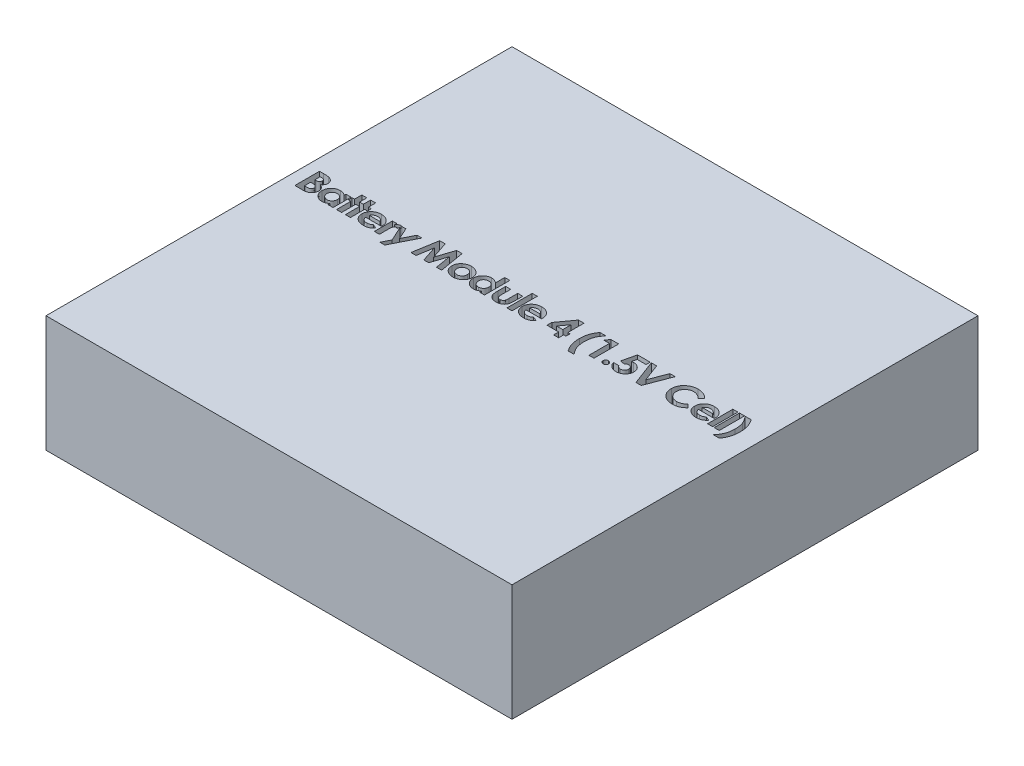
SolidWorks part; units mm, degrees
ref_plane "Front Plane" through (0, 0, 0) normal (0, 0, 1) x (1, 0, 0)
ref_plane "Top Plane" through (0, 0, 0) normal (0, 1, 0) x (1, 0, 0)
ref_plane "Right Plane" through (0, 0, 0) normal (1, 0, 0) x (0, 0, -1)
sketch "Sketch1" plane through (0, 0, 0) normal (0, 1, 0) x (1, 0, 0)
  line L1 (0, 0) -> (60, 0)
  line L2 (0, 0) -> (0, -60)
  line L3 (0, -60) -> (60, -60)
  line L4 (60, 0) -> (60, -60)
  dimension "D1" = 60
  dimension "D2" = 60
extrude "Boss-Extrude1" add sketch "Sketch1" along normal blind 15
sketch "Sketch2" plane through (0, 15, 0) normal (0, 1, 0) x (1, 0, 0)
  text T0 "<b>Battery Module 4 (1.5V Cell)</b>" font "Century Gothic" height 3.175
extrude "Cut-Extrude1" cut sketch "Sketch2" against normal blind 5
